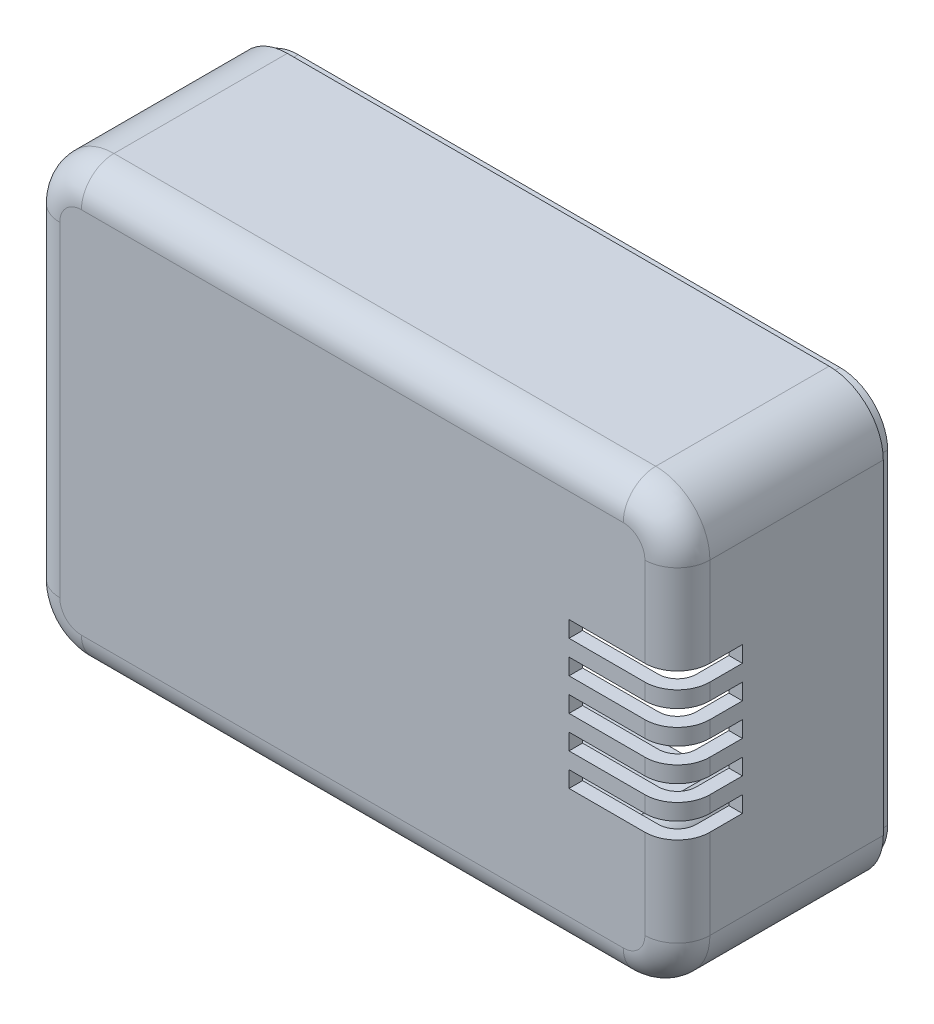
SolidWorks part; units mm, degrees
ref_plane "前视基准面" through (0, 0, 0) normal (0, 0, 1) x (1, 0, 0)
ref_plane "上视基准面" through (0, 0, 0) normal (0, 1, 0) x (1, 0, 0)
ref_plane "右视基准面" through (0, 0, 0) normal (1, 0, 0) x (0, 0, -1)
sketch "草图1" plane through (0, 0, 0) normal (0, 0, 1) x (1, 0, 0)
  line L0 (-50, -40) -> (50, -40)
  line L1 (60, -30) -> (60, 30)
  line L2 (50, 40) -> (-50, 40)
  line L3 (-60, 30) -> (-60, -30)
  arc A0 (-60, -30) -> (-50, -40) centre (-50, -30) ccw
  arc A1 (50, -40) -> (60, -30) centre (50, -30) ccw
  arc A2 (60, 30) -> (50, 40) centre (50, 30) ccw
  arc A3 (-50, 40) -> (-60, 30) centre (-50, 30) ccw
extrude "凸台-拉伸1" add sketch "草图1" along normal blind 40
fillet "圆角1" radius 6 8 edges at (-57.0711, -37.0711, 40) (57.0711, -37.0711, 40) (-57.0711, 37.0711, 40) (57.0711, 37.0711, 40) (-60, 0, 40) (60, 0, 40) (0, -40, 40) (0, 40, 40)
shell "抽壳1" thickness 2.5
sketch "草图2" plane through (0, 0, 0) normal (0, 0, 1) x (1, 0, 0)
  line L0 (-50, -45) -> (50, -45)
  line L1 (65, -30) -> (65, 30)
  line L2 (50, 45) -> (-50, 45)
  line L3 (-65, 30) -> (-65, -30)
  line L4 (-50, -38.8) -> (50, -38.8)
  line L5 (58.8, -30) -> (58.8, 30)
  line L6 (50, 38.8) -> (-50, 38.8)
  line L7 (-58.8, 30) -> (-58.8, -30)
  arc A0 (-65, -30) -> (-50, -45) centre (-50, -30) ccw
  arc A1 (50, -45) -> (65, -30) centre (50, -30) ccw
  arc A2 (65, 30) -> (50, 45) centre (50, 30) ccw
  arc A3 (-50, 45) -> (-65, 30) centre (-50, 30) ccw
  arc A4 (-58.8, -30) -> (-50, -38.8) centre (-50, -30) ccw
  arc A5 (50, -38.8) -> (58.8, -30) centre (50, -30) ccw
  arc A6 (58.8, 30) -> (50, 38.8) centre (50, 30) ccw
  arc A7 (-50, 38.8) -> (-58.8, 30) centre (-50, 30) ccw
extrude "切除-拉伸1" cut sketch "草图2" along normal blind 2
ref_plane "基准面1" through (0, -12, 0) normal (0, 1, 0) x (1, 0, 0)
sketch "草图5" plane through (0, -12, 0) normal (0, 1, 0) x (1, 0, 0)
  line L0 (40, -28) -> (65, -28)
  line L1 (65, -28) -> (65, -45)
  line L2 (65, -45) -> (40, -45)
  line L3 (40, -45) -> (40, -28)
extrude "切除-拉伸4" cut sketch "草图5" against normal mid plane 3
pattern_linear "阵列(线性)1" count 5 spacing 6 along (0, 1, 0) of "切除-拉伸4"
ref_plane "基准面2" through (0, 0, 5) normal (0, 0, 1) x (1, 0, 0)
sketch "草图6" plane through (0, 0, 5) normal (0, 0, 1) x (1, 0, 0)
  circle A0 centre (45, 25) radius 4
  circle A1 centre (45, -25) radius 4
  circle A2 centre (-45, 25) radius 4
  circle A3 centre (-45, -25) radius 4
extrude "凸台-拉伸2" add sketch "草图6" along normal blind 32.5
sketch "草图7" plane through (0, 0, 5) normal (0, 0, 1) x (1, 0, 0)
  circle A0 centre (45, 25) radius 1.25
  circle A1 centre (45, -25) radius 1.25
  circle A2 centre (-45, 25) radius 1.25
  circle A3 centre (-45, -25) radius 1.25
extrude "切除-拉伸5" cut sketch "草图7" along normal blind 12
